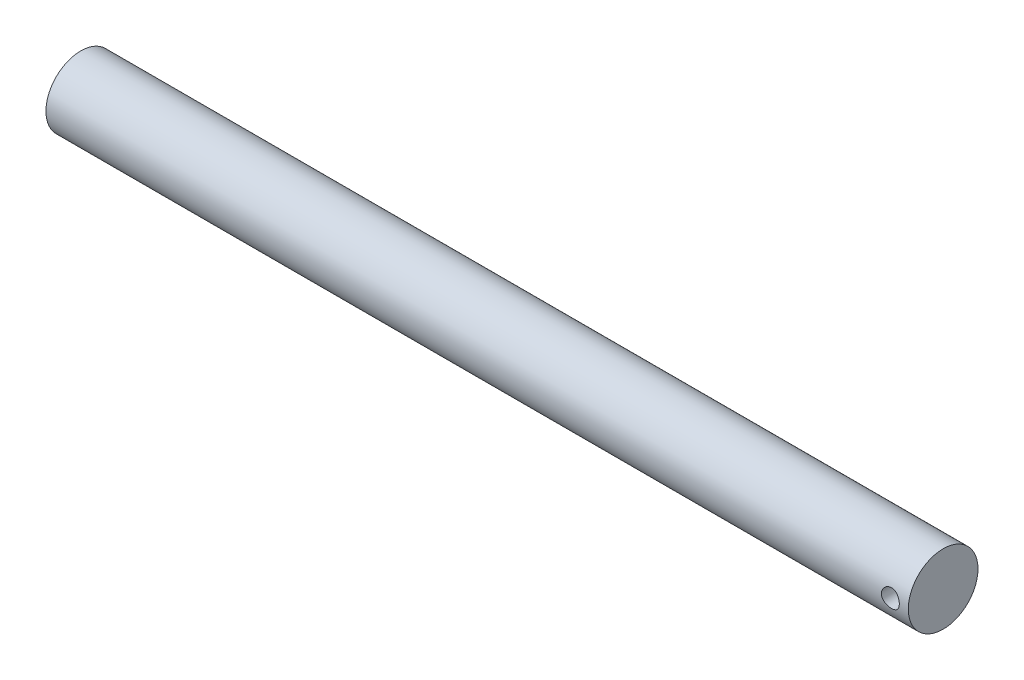
SolidWorks part; units mm, degrees
ref_plane "Front Plane" through (0, 0, 0) normal (0, 0, 1) x (1, 0, 0)
ref_plane "Top Plane" through (0, 0, 0) normal (0, 1, 0) x (1, 0, 0)
ref_plane "Right Plane" through (0, 0, 0) normal (1, 0, 0) x (0, 0, -1)
sketch "Sketch1" plane through (0, 0, 0) normal (1, 0, 0) x (0, 0, -1)
  circle A0 centre (0, 0) radius 4.85
  dimension "D1" = 9.7
extrude "Boss-Extrude1" add sketch "Sketch1" along normal blind 120
sketch "Sketch2" plane through (0, 0, 0) normal (0, 0, 1) x (1, 0, 0)
  line L1 (120, -4.85) -> (120, 4.85) construction
  circle A0 centre (117.5, 0) radius 1.25
  dimension "D1" = 2.5
  dimension "D2" = 2.5
extrude "Cut-Extrude1" cut sketch "Sketch2" against normal through all both and the other way through all
scale "Scale1" scale about centroid uniform scaling yes scale factor 1.5
